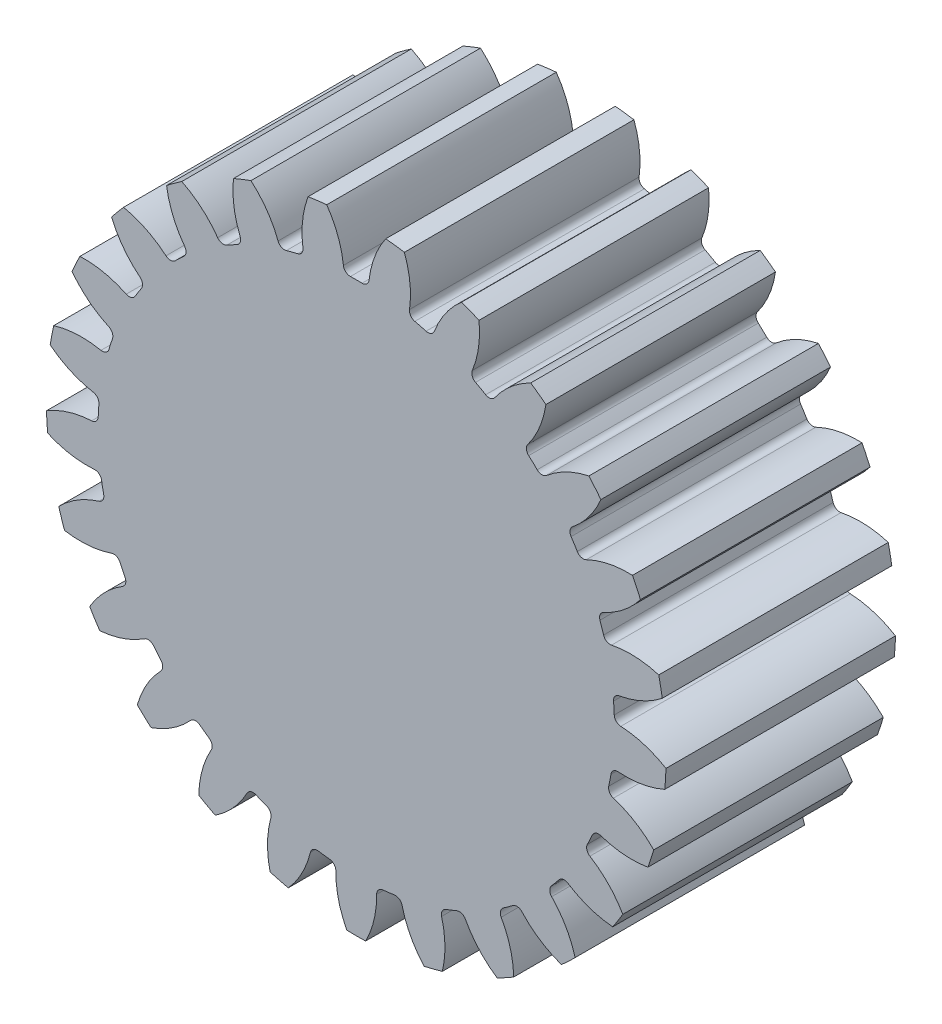
SolidWorks part; units mm, degrees
ref_plane "Front Plane" through (0, 0, 0) normal (0, 0, 1) x (1, 0, 0)
ref_plane "Top Plane" through (0, 0, 0) normal (0, 1, 0) x (1, 0, 0)
ref_plane "Right Plane" through (0, 0, 0) normal (1, 0, 0) x (0, 0, -1)
sketch "Sketch1" plane through (0, 0, 0) normal (0, 0, 1) x (1, 0, 0)
  circle A0 centre (0, 0) radius 27
  circle A1 centre (0, 0) radius 25
  circle A2 centre (0, 0) radius 22.5
  dimension "D1" = 45
  dimension "D2" = 50
  dimension "D3" = 54
extrude "Boss-Extrude1" add sketch "Sketch1" along normal mid plane 20 contours A2 | A1 A2 | A0 A1
sketch "Sketch2" plane through (0, 0, 0) normal (0, 0, 1) x (1, 0, 0)
  line L0 (0, -31.4954) -> (0, 43.6882) construction
  line L1 (0, 43.6882) -> (0, -31.4954) construction
  line L2 (1.5698, 24.9507) -> (-1.5698, 24.9507) construction
  line L3 (0, 0) -> (-1.072, 22.4744) construction
  line L4 (0, 20.6378) -> (-2.6344, 27.8758) construction
  line L5 (0, 0) -> (3.5093, 27.7792) construction
  line L6 (1.5698, 24.9507) -> (4.6845, 24.5572) construction
  arc A1 (-3.3153, 27.803) -> (-1.072, 22.4744) centre (-9.4743, 22.0737) cw
  circle A2 centre (0, 0) radius 28
  circle A3 centre (0, 0) radius 28
  circle A4 centre (0, 0) radius 22.5 construction
  circle A5 centre (0, 0) radius 27 construction
  circle A6 centre (0, 0) radius 25 construction
  circle A7 centre (0, 0) radius 22.5
  circle A8 centre (0, 0) radius 27
  circle A9 centre (0, 0) radius 25
  arc A10 (3.3153, 27.803) -> (1.072, 22.4744) centre (9.4743, 22.0737) ccw
  dimension "D2" = 20
  dimension "D3" = 7.2
  dimension "D1" = 1
extrude "Cut-Extrude2" cut sketch "Sketch2" against normal through all both and the other way through all contours A10 A3 A1 A8 | A10 A8 A1 A9 | A10 A9 A1 A7
fillet "Fillet1" radius 0.6 2 edges at (-1.072, 22.4744, 0) (1.072, 22.4744, 0)
pattern_circular "CirPattern1" count 25 over 360 about axis through (0, 0, 0) along (0, 0, 1) of "Cut-Extrude2", "Fillet1"
scale "Scale1" scale about centroid uniform scaling yes scale factor 0.6
equation "\"m\"= 2mm'module"
equation "\"p\"= 20'pressure angle"
equation "\"n\"= 25'number of teeth"
equation "\"d\"= \"n\" * \"m\"'pitch circle diameter"
equation "\"o\"= \"m\" * ( \"n\" + 2 )'addendum circle diameter"
equation "\"i\"= \"o\" - \"m\" * IIF ( \"m\" = > 1.25 , 2.25 , 2.4 ) * 2'dedendum circle diameter"
equation "\"D1@Sketch1\"=\"i\""
equation "\"D2@Sketch1\"=\"d\""
equation "\"D3@Sketch1\"=\"o\""
equation "\"D2@Sketch2\"=\"p\""
equation "\"D3@Sketch2\"=180/\"n\""
equation "\"D1@Fillet1\"=.3*\"m\""
equation "\"D1@CirPattern1\"=\"n\""
